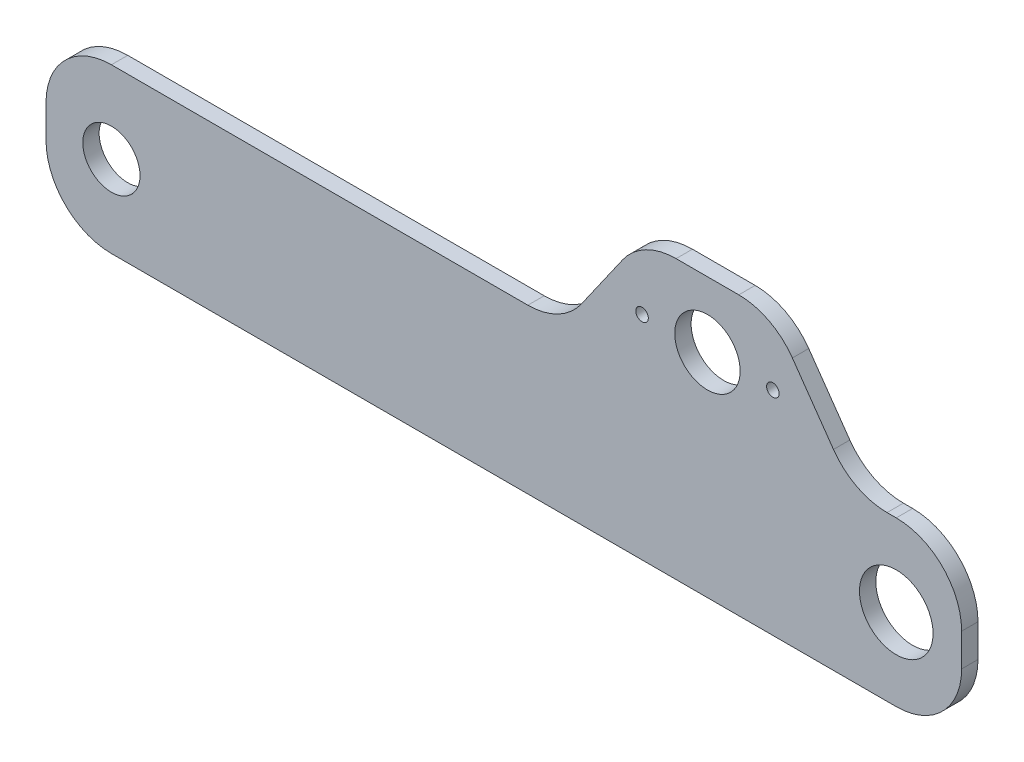
SolidWorks part; units mm, degrees
material "ABS PC"
ref_plane "Front Plane" through (0, 0, 0) normal (0, 0, 1) x (1, 0, 0)
ref_plane "Top Plane" through (0, 0, 0) normal (0, 1, 0) x (1, 0, 0)
ref_plane "Right Plane" through (0, 0, 0) normal (1, 0, 0) x (0, 0, -1)
sketch "Layout" plane through (0, 0, 0) normal (0, 0, 1) x (1, 0, 0)
  line L0 (-329.0442, 0) -> (309.3606, 0) construction
  line L1 (36.9648, 44.45) -> (341.7648, 44.45)
  line L2 (11.5648, 69.85) -> (11.5648, 82.55)
  line L3 (36.9648, 107.95) -> (198.6989, 107.95)
  line L4 (367.1648, 69.85) -> (367.1648, 82.55)
  line L8 (11.5648, 76.2) -> (367.1648, 76.2) construction
  line L9 (243.0455, 127) -> (293.8455, 127) construction
  line L10 (219.5053, 118.7812) -> (235.4614, 141.5688)
  line L11 (256.2679, 152.4) -> (280.6231, 152.4)
  line L12 (301.4296, 141.5688) -> (317.3857, 118.7812)
  line L14 (338.1921, 107.95) -> (341.7648, 107.95)
  circle A0 centre (36.9648, 76.2) radius 11.1125
  circle A1 centre (341.7648, 76.2) radius 14.2875
  circle A3 centre (268.4455, 127) radius 25.4 construction
  circle A4 centre (243.0455, 127) radius 2.4384
  circle A5 centre (293.8455, 127) radius 2.4384
  circle A6 centre (341.7648, 76.2) radius 38.1 construction
  circle A7 centre (268.4455, 127) radius 12.7
  arc A8 (341.7648, 44.45) -> (367.1648, 69.85) centre (341.7648, 69.85) ccw
  arc A9 (341.7648, 107.95) -> (367.1648, 82.55) centre (341.7648, 82.55) cw
  arc A10 (317.3857, 118.7812) -> (338.1921, 107.95) centre (338.1921, 133.35) ccw
  arc A11 (280.6231, 152.4) -> (301.4296, 141.5688) centre (280.6231, 127) cw
  arc A12 (235.4614, 141.5688) -> (256.2679, 152.4) centre (256.2679, 127) cw
  arc A13 (219.5053, 118.7812) -> (198.6989, 107.95) centre (198.6989, 133.35) cw
  arc A14 (36.9648, 44.45) -> (11.5648, 69.85) centre (36.9648, 69.85) cw
  arc A15 (11.5648, 82.55) -> (36.9648, 107.95) centre (36.9648, 82.55) cw
  point P31 (367.1648, 107.95)
  point P34 (324.9697, 107.95)
  point P37 (293.8455, 152.4)
  point P40 (243.0455, 152.4)
  point P47 (11.5648, 107.95)
  dimension "D9" = 22.225
  dimension "D10" = 28.575
  dimension "D11" = 76.2
  dimension "D12" = 50.8
  dimension "D15" = 4.8768
  dimension "D16" = 25.4
  dimension "D4" = 25.4
  dimension "D2" = 63.5
  dimension "D3" = 355.6
  dimension "D8" = 25.4
  dimension "D13" = 89.1984
  dimension "D14" = 25.4
  dimension "D17" = 50.8
  dimension "D18" = 44.45
  dimension "D19" = 235
  dimension "D20" = 25.4
  dimension "D21" = 50.8
extrude "Boss-Extrude1" add sketch "Layout" along normal blind 6.35
